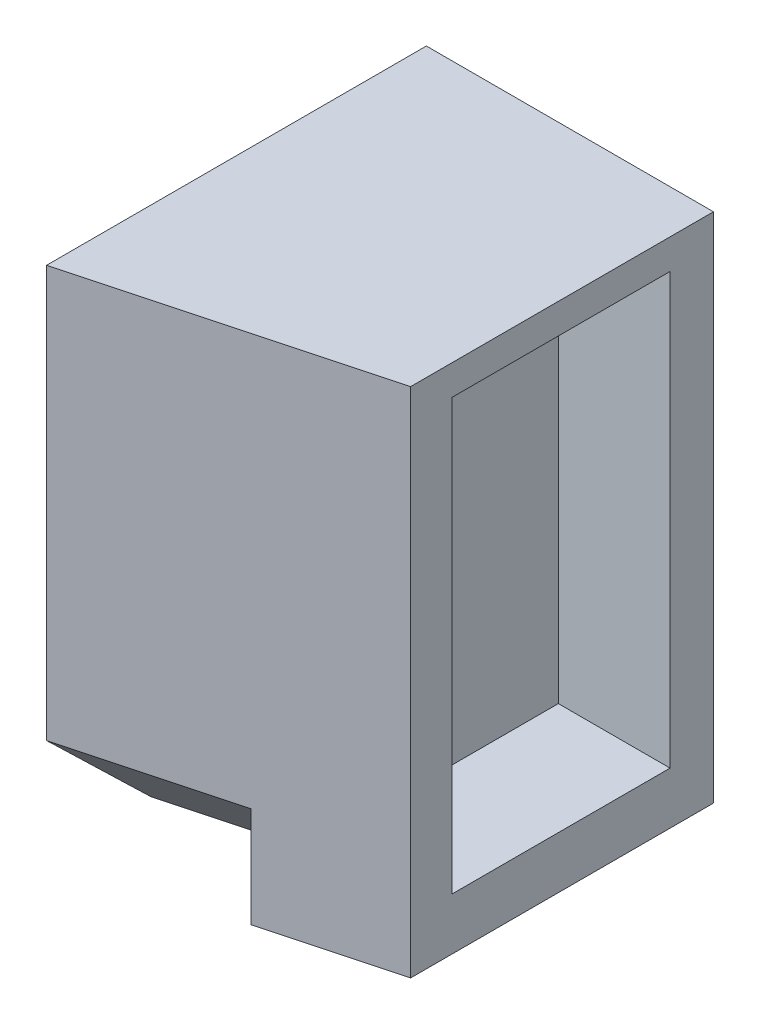
SolidWorks part; units mm, degrees
ref_plane "Front Plane" through (0, 0, 0) normal (0, 0, 1) x (1, 0, 0)
ref_plane "Top Plane" through (0, 0, 0) normal (0, 1, 0) x (1, 0, 0)
ref_plane "Right Plane" through (0, 0, 0) normal (1, 0, 0) x (0, 0, -1)
sketch3d "3DSketch1"
  line L2 (0, 582.2226, 215.9) -> (0, 0, 215.9) construction
  line L3 (326.399, 0, 431.8) -> (326.399, 0, 0) construction
  line L6 (0, 0, 0) -> (0, 582.2226, 0) construction
  line L7 (326.399, 582.2226, 431.8) -> (326.399, 582.2226, 0) construction
  line L8 (326.399, 582.2226, 0) -> (326.399, 0, 0) construction
  line L9 (0, 0, 431.8) -> (0, 582.2226, 431.8) construction
  line L10 (326.399, 582.2226, 431.8) -> (0, 582.2226, 431.8) construction
  line L11 (326.399, 0, 431.8) -> (326.399, 582.2226, 431.8) construction
  line L12 (0, 582.2226, 431.8) -> (0, 582.2226, 0) construction
  line L13 (326.399, 0, 431.8) -> (0, 0, 431.8) construction
  line L14 (326.399, 582.2226, 0) -> (0, 582.2226, 0) construction
  line L15 (0, 0, 431.8) -> (0, 0, 0) construction
  line L16 (326.399, 0, 0) -> (0, 0, 0) construction
  line L17 (0, 209.55, 215.9) -> (173.99, 209.55, 215.9) construction
  line L18 (0, 412.75, 291.084) -> (0, 563.88, 291.084) construction
  line L19 (0, 412.75, 291.084) -> (0, 412.75, 140.716) construction
  line L20 (0, 412.75, 140.716) -> (0, 563.88, 140.716) construction
  line L21 (0, 563.88, 291.084) -> (0, 563.88, 140.716) construction
  line L22 (0, 412.75, 291.084) -> (0, 563.88, 140.716) construction
  line L23 (0, 412.75, 140.716) -> (0, 563.88, 291.084) construction
  circle A0 centre (0, 209.55, 215.9) radius 196.85 construction
  point P11 (196.85, 209.55, 215.9)
  point P14 (0, 406.4, 215.9)
  point P15 (0, 12.7, 215.9)
  point P16 (0, 412.75, 215.9)
  point P17 (0, 488.315, 215.9)
  point P22 (0, 0, 0)
  point P24 (0, 0, 0)
  point P25 (0, 0, 0)
  dimension "D1" = 326.399
  dimension "D4" = 393.7
  dimension "D2" = 431.8
  dimension "D3" = 582.2226
  dimension "D5" = 12.7
  dimension "D6" = 150.368
  dimension "D7" = 151.13
  dimension "D8" = 6.35
  dimension "D9" = 173.99
sketch "Sketch1" plane through (0, 0, 0) normal (1, 0, 0) x (0, 0, -1)
  line L0 (-409.5424, 709.2226) -> (-420.6712, 582.2226)
  line L4 (-409.5424, 709.2226) -> (-215.9, 709.2226)
  line L5 (-215.9, 709.2226) -> (-215.9, 582.2226) construction
  line L6 (-431.8, 582.2226) -> (0, 582.2226) construction
  line L8 (-420.6712, 582.2226) -> (-431.8, 455.2226)
  line L9 (-431.8, 0) -> (-431.8, 582.2226) construction
  point P0 (-299.3658, 631.7037)
  dimension "D1" = 127
  dimension "D2" = 193.6424
sketch "Sketch2" plane through (0, 0, 0) normal (0, 1, 0) x (1, 0, 0)
  line L0 (0, -431.8) -> (326.399, -344.3417)
  line L1 (326.399, -431.8) -> (326.399, 0) construction
  line L3 (0, -431.8) -> (0, 0) construction
  line L5 (326.399, -344.3417) -> (326.399, 0)
  line L6 (326.399, 0) -> (0, 0)
  line L7 (0, 0) -> (0, -431.8)
  dimension "D1" = 75
extrude "Boss-Extrude1" add sketch "Sketch2" along normal up to vertex (582.2226 mm away)
sketch "Sketch3" plane through (326.399, 0, 0) normal (1, 0, 0) x (0, 0, -1)
  line L1 (-49.3464, 59.1545) -> (-296.9964, 59.1545)
  line L2 (-49.3464, 59.1545) -> (-49.3464, 548.1045)
  line L3 (-49.3464, 548.1045) -> (-296.9964, 548.1045)
  line L4 (-296.9964, 59.1545) -> (-296.9964, 548.1045)
  line L5 (-49.3464, 59.1545) -> (-296.9964, 548.1045) construction
  line L6 (-49.3464, 548.1045) -> (-296.9964, 59.1545) construction
  point P0 (-173.1714, 303.6295)
  point P5 (-173.1714, 303.6295)
  dimension "D1" = 247.65
  dimension "D2" = 488.95
extrude "Cut-Extrude1" cut sketch "Sketch3" against normal blind 127
sketch "Sketch4" plane through (0, 0, 0) normal (1, 0, 0) x (0, -1, 0)
  line L1 (-309.55, -340.9) -> (-109.55, -340.9)
  line L2 (-309.55, -340.9) -> (-309.55, -90.9)
  line L3 (-309.55, -90.9) -> (-109.55, -90.9)
  line L4 (-109.55, -340.9) -> (-109.55, -90.9)
  line L5 (-309.55, -340.9) -> (-109.55, -90.9) construction
  line L6 (-309.55, -90.9) -> (-109.55, -340.9) construction
  point P0 (-209.55, -215.9)
  point P5 (0, 0)
  point P6 (-141.6696, -165.947)
  point P7 (-222.25, -215.9)
  dimension "D1" = 200
  dimension "D2" = 250
extrude "Cut-Extrude2" cut sketch "Sketch4" along normal blind 100
sketch "Sketch5" plane through (0, 0, 0) normal (-1, 0, 0) x (0, 0, 1)
  line L1 (265.9, 438.315) -> (165.9, 438.315)
  line L2 (265.9, 438.315) -> (265.9, 538.315)
  line L3 (265.9, 538.315) -> (165.9, 538.315)
  line L4 (165.9, 438.315) -> (165.9, 538.315)
  line L5 (265.9, 438.315) -> (165.9, 538.315) construction
  line L6 (265.9, 538.315) -> (165.9, 438.315) construction
  point P0 (215.9, 488.315)
  dimension "D1" = 100
  dimension "D2" = 100
extrude "Cut-Extrude3" cut sketch "Sketch5" against normal blind 100
sketch "Sketch6" plane through (0, 0, 0) normal (-1, 0, 0) x (0, 0, 1)
  line L0 (0, 114.3) -> (114.3, 0)
  line L1 (0, 0) -> (0, 582.2226) construction
  line L2 (431.8, 0) -> (0, 0) construction
  line L3 (114.3, 0) -> (0, 0)
  line L4 (0, 0) -> (0, 114.3)
  dimension "D1" = 114.3
  dimension "D2" = 114.3
extrude "Cut-Extrude4" cut sketch "Sketch6" against normal blind 172
ref_plane "Plane1" through (-107.95, 0, 28.9251) normal (0.9659, 0, -0.2588) x (0, 1, 0)
sketch "Sketch7" plane through (-107.95, 0, 28.9251) normal (0.9659, 0, -0.2588) x (0, 1, 0)
  line L0 (0, 417.0868) -> (114.3, 417.0868)
  line L1 (0, 417.0868) -> (582.2226, 417.0868) construction
  line L2 (114.3, 417.0868) -> (0, 302.7868)
  line L3 (0, 302.7868) -> (0, 417.0868)
  dimension "D1" = 114.3
  dimension "D2" = 114.3
extrude "Cut-Extrude5" cut sketch "Sketch7" along normal blind 190
equation "\"depth\"= \"vol\" / \"width\" / \"height\""
equation "\"D1@3DSketch1\"=\"depth\""
equation "\"width\"= 15.5 + 2 * \"gap\""
equation "\"D2@3DSketch1\"=\"width\""
equation "\"height\"= \"width\" * ( 1 + 5 ^ ( 1 / 2 ) ) / 2.4"
equation "\"D3@3DSketch1\"=\"height\""
equation "\"vol\" = 61 * ( 50 + 5.2 + 0.5 + 0.5 + 3 ) + ( 19.25 * 9.75 * 5.5 ) + 364"
equation "\"gap\"= .75"
equation "\"WedgeVol\"= \"height\" * 0.5 * sin ( 15 ) * \"depth\" ^ 2'261"
equation "\"topHeight\"=5"
equation "\"topWidth\" = \"WedgeVol\" / \"depth\" / \"topHeight\""
equation "\"D2@Sketch1\"=\"topWidth\""
equation "\"D1@Sketch1\"=\"topHeight\""
